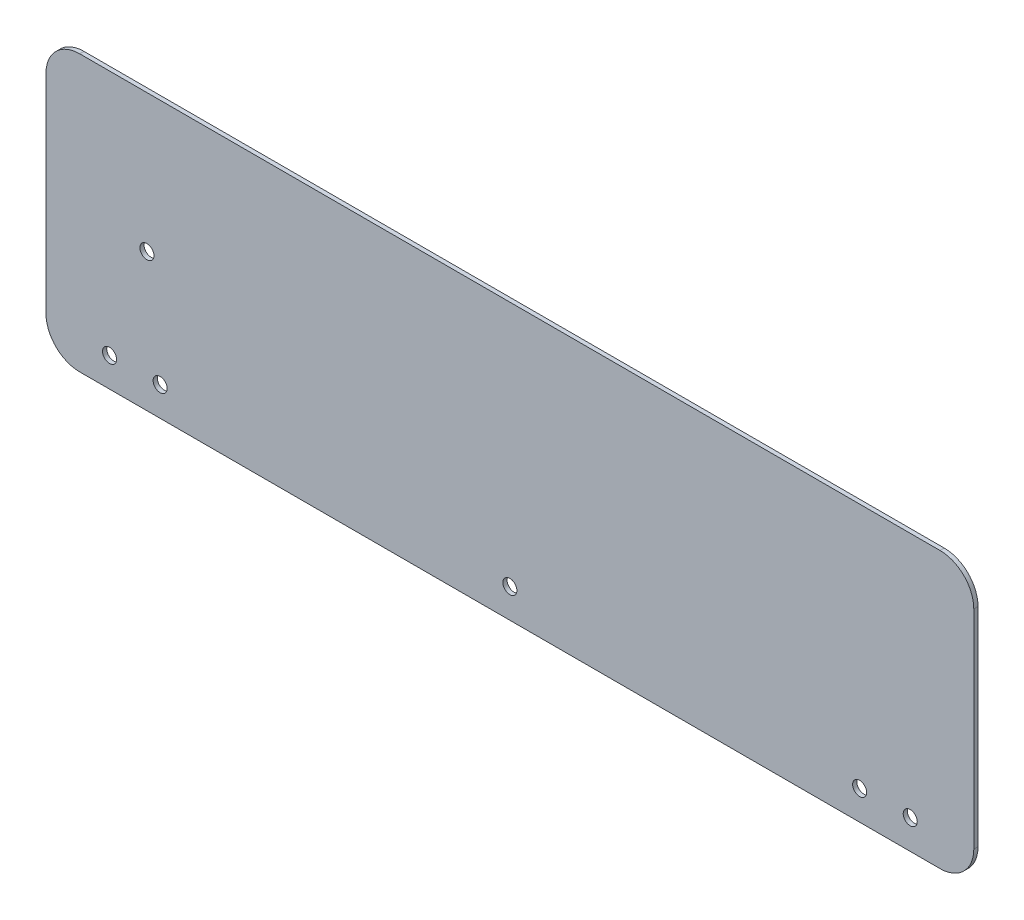
SolidWorks part; units mm, degrees
ref_plane "Front" through (0, 0, 0) normal (0, 0, 1) x (1, 0, 0)
ref_plane "Top" through (0, 0, 0) normal (0, 1, 0) x (1, 0, 0)
ref_plane "Right" through (0, 0, 0) normal (1, 0, 0) x (0, 0, -1)
sketch "Sketch1" plane through (0, 0, 0) normal (0, 0, 1) x (1, 0, 0)
  line L8 (19.431, 6.223) -> (-19.431, 6.223)
  line L9 (-20.955, 4.699) -> (-20.955, -4.699)
  line L10 (-19.431, -6.223) -> (19.431, -6.223)
  line L11 (20.955, -4.699) -> (20.955, 4.699)
  circle A5 centre (0, -4.9022) radius 0.1715 construction
  circle A6 centre (18.0848, -4.9022) radius 0.1715 construction
  circle A7 centre (15.7988, -4.9022) radius 0.1715 construction
  arc A8 (-19.431, 6.223) -> (-20.955, 4.699) centre (-19.431, 4.699) ccw
  arc A9 (-20.955, -4.699) -> (-19.431, -6.223) centre (-19.431, -4.699) ccw
  arc A10 (19.431, -6.223) -> (20.955, -4.699) centre (19.431, -4.699) ccw
  arc A11 (20.955, 4.699) -> (19.431, 6.223) centre (19.431, 4.699) ccw
  circle A12 centre (-16.3957, 0) radius 0.1651 construction
  circle A13 centre (-15.7988, -4.9022) radius 0.1715 construction
  circle A14 centre (-18.0848, -4.9022) radius 0.1715 construction
  circle A15 centre (0, -4.9022) radius 0.1714 construction
  circle A16 centre (18.0848, -4.9022) radius 0.1714 construction
  circle A17 centre (15.7988, -4.9022) radius 0.1714 construction
  circle A18 centre (-16.3957, 0) radius 0.1651 construction
  circle A19 centre (-15.7988, -4.9022) radius 0.1715 construction
  circle A20 centre (-18.0848, -4.9022) radius 0.1715 construction
  circle A21 centre (18.0848, -4.9022) radius 0.3175
  circle A22 centre (15.7988, -4.9022) radius 0.3175
  circle A23 centre (0, -4.9022) radius 0.3175
  circle A24 centre (-16.3957, 0) radius 0.3175
  circle A25 centre (-15.7988, -4.9022) radius 0.3175
  circle A26 centre (-18.0848, -4.9022) radius 0.3175
  dimension "D2" = 12.446
  dimension "D1" = 1.524
  dimension "D4" = 0.635
  dimension "D3" = 41.91
extrude "Boss-Extrude1" add sketch "Sketch1" against normal blind 0.1905 separate body
